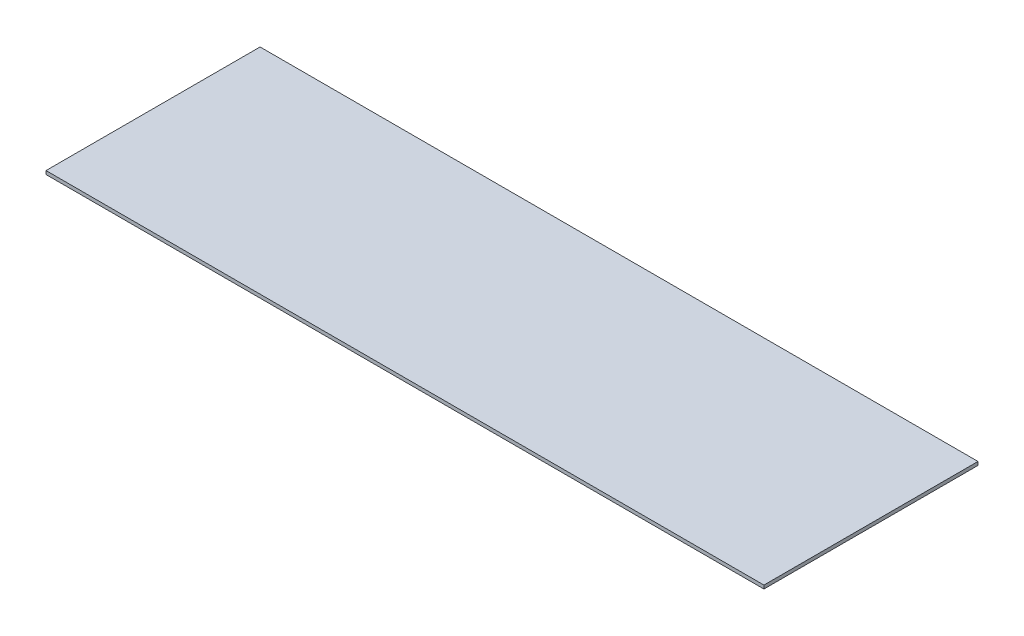
SolidWorks part; units mm, degrees
ref_plane "Front Plane" through (0, 0, 0) normal (0, 0, 1) x (1, 0, 0)
ref_plane "Top Plane" through (0, 0, 0) normal (0, 1, 0) x (1, 0, 0)
ref_plane "Right Plane" through (0, 0, 0) normal (1, 0, 0) x (0, 0, -1)
sketch "Sketch1" plane through (0, 0, 0) normal (0, 1, 0) x (1, 0, 0)
  line L1 (0, 0) -> (-657.606, 0)
  line L2 (0, 0) -> (0, 196.088)
  line L3 (0, 196.088) -> (-657.606, 196.088)
  line L4 (-657.606, 0) -> (-657.606, 196.088)
  line L8 (-657.606, 196.088) -> (-652.272, 196.088)
  dimension "D1" = 657.606
  dimension "D2" = 196.088
extrude "Boss-Extrude4" add sketch "Sketch1" along normal blind 3.175
